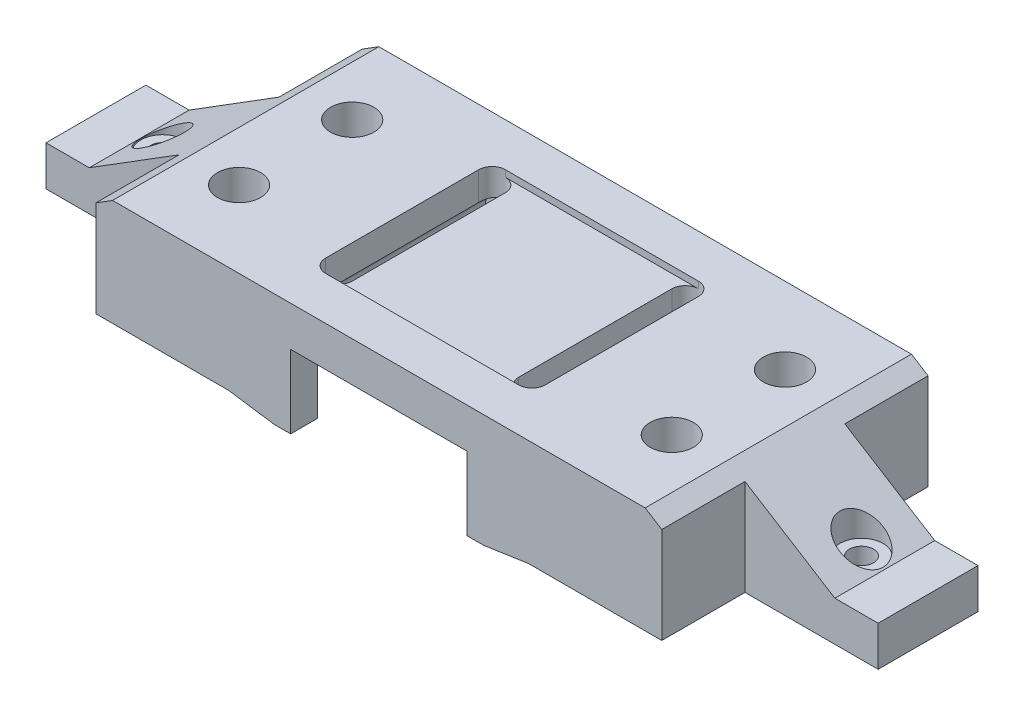
SolidWorks part; units mm, degrees
ref_plane "Front Plane" through (0, 0, 0) normal (0, 0, 1) x (1, 0, 0)
ref_plane "Top Plane" through (0, 0, 0) normal (0, 1, 0) x (1, 0, 0)
ref_plane "Right Plane" through (0, 0, 0) normal (1, 0, 0) x (0, 0, -1)
sketch "Sketch1" plane through (0, 0, 0) normal (0, 1, 0) x (1, 0, 0)
  line L0 (42.5, 20) -> (42.5, 7.5)
  line L1 (-42.5, 20) -> (42.5, 20)
  line L3 (-42.5, -20) -> (42.5, -20)
  line L5 (-42.5, 20) -> (42.5, -20) construction
  line L6 (-42.5, -20) -> (42.5, 20) construction
  line L7 (42.5, 7.5) -> (62.5, 7.5)
  line L8 (62.5, 7.5) -> (62.5, -7.5)
  line L9 (62.5, -7.5) -> (42.5, -7.5)
  line L10 (42.5, -7.5) -> (42.5, -20)
  line L11 (0, 0) -> (0, -116.996) construction
  line L12 (-42.5, -7.5) -> (-42.5, -20)
  line L13 (-62.5, -7.5) -> (-42.5, -7.5)
  line L14 (-62.5, 7.5) -> (-62.5, -7.5)
  line L15 (-42.5, 7.5) -> (-62.5, 7.5)
  line L16 (-42.5, 20) -> (-42.5, 7.5)
  circle A0 centre (-52.5, 0) radius 1.8
  circle A1 centre (-32.5, 8.5) radius 1.8
  circle A2 centre (-32.5, -8.5) radius 1.8
  circle A3 centre (32.5, -8.5) radius 1.8
  circle A4 centre (52.5, 0) radius 1.8
  circle A5 centre (32.5, 8.5) radius 1.8
  point P0 (0, 0)
  dimension "D6" = 3.6
  dimension "D1" = 85
  dimension "D2" = 40
  dimension "D3" = 20
  dimension "D4" = 15
  dimension "D5" = 12.5
  dimension "D7" = 7.5
  dimension "D8" = 10
  dimension "D9" = 10
  dimension "D10" = 1
  dimension "D11" = 10
  dimension "D12" = 1
extrude "Boss-Extrude1" add sketch "Sketch1" along normal blind 6
sketch "Sketch2" plane through (0, 0, -20) normal (0, 0, -1) x (-1, 0, 0)
  line L0 (-56, 6) -> (-40, 16)
  line L1 (-42.5, 6) -> (42.5, 6) construction
  line L2 (-40, 16) -> (40, 16)
  line L3 (40, 16) -> (56, 6)
  line L4 (-62.5, 6) -> (-42.5, 6) construction
  line L5 (-56, 6) -> (56, 6)
  dimension "D1" = 80
  dimension "D2" = 10
  dimension "D3" = 112
  dimension "D4" = 16
  dimension "D5" = 6.5
extrude "Boss-Extrude2" add sketch "Sketch2" against normal up to surface (40 mm away) up to face at (0, 3, 20)
sketch "Sketch3" plane through (0, 6, 0) normal (0, -1, 0) x (1, 0, 0)
  line L0 (-62.5, 7.5) -> (-42.5, 7.5) construction
  line L1 (-56, 20) -> (-42.5, 20)
  line L2 (-56, 20) -> (-56, 7.5)
  line L3 (-56, 7.5) -> (-42.5, 7.5)
  line L4 (-42.5, 20) -> (-42.5, 7.5)
  line L5 (-56, 7.5) -> (-42.5, 7.5) construction
  line L6 (62.5, -7.5) -> (42.5, -7.5) construction
  line L7 (-56, -7.5) -> (-42.5, -7.5)
  line L8 (-56, -7.5) -> (-56, -20)
  line L9 (-56, -20) -> (-42.5, -20)
  line L10 (-42.5, -7.5) -> (-42.5, -20)
  line L11 (42.5, -20) -> (56, -20)
  line L12 (42.5, -20) -> (42.5, -7.5)
  line L13 (42.5, -7.5) -> (56, -7.5)
  line L14 (56, -20) -> (56, -7.5)
  line L15 (56, -7.5) -> (56, -20) construction
  line L17 (56, 7.5) -> (42.5, 7.5)
  line L18 (56, 7.5) -> (56, 20)
  line L19 (56, 20) -> (42.5, 20)
  line L20 (42.5, 7.5) -> (42.5, 20)
  circle A0 centre (52.5, 0) radius 1.8 construction
  circle A1 centre (32.5, -8.5) radius 1.8 construction
  circle A2 centre (32.5, 8.5) radius 1.8 construction
  circle A3 centre (-32.5, -8.5) radius 1.8 construction
  circle A4 centre (-52.5, 0) radius 1.8 construction
  circle A5 centre (-32.5, 8.5) radius 1.8 construction
  circle A6 centre (52.5, 0) radius 1.8
  circle A7 centre (32.5, -8.5) radius 1.8
  circle A8 centre (32.5, 8.5) radius 1.8
  circle A9 centre (-32.5, -8.5) radius 1.8
  circle A10 centre (-52.5, 0) radius 1.8
  circle A11 centre (-32.5, 8.5) radius 1.8
extrude "Cut-Extrude1" cut sketch "Sketch3" against normal up to next
sketch "Sketch4" plane through (0, 16, 0) normal (0, 1, 0) x (1, 0, 0)
  circle A0 centre (-32.5, 8.5) radius 3.25
  circle A1 centre (-52.5, 0) radius 3.25
  circle A2 centre (-32.5, -8.5) radius 3.25
  circle A3 centre (32.5, 8.5) radius 3.25
  circle A4 centre (32.5, -8.5) radius 3.25
  circle A5 centre (52.5, 0) radius 3.25
  dimension "D1" = 6.5
extrude "Cut-Extrude2" cut sketch "Sketch4" against normal up to surface (10 mm away) up to face at (-59.25, 6, 0)
sketch "Sketch5" plane through (0, 0, -20) normal (0, 0, -1) x (-1, 0, 0)
  line L0 (-22.5, 0) -> (-16, 10)
  line L1 (-42.5, 0) -> (42.5, 0) construction
  line L2 (-16, 10) -> (16, 10)
  line L3 (16, 10) -> (22.5, 0)
  line L4 (22.5, 0) -> (-22.5, 0)
  dimension "D5" = 6.5
  dimension "D1" = 45
  dimension "D2" = 20
  dimension "D3" = 10
  dimension "D4" = 32
extrude "Cut-Extrude3" cut sketch "Sketch5" against normal up to next
sketch "Sketch6" plane through (0, 10, 0) normal (0, -1, 0) x (1, 0, 0)
  line L1 (-17.5, 13.5) -> (17.5, 13.5)
  line L2 (-17.5, 13.5) -> (-17.5, -13.5)
  line L3 (-17.5, -13.5) -> (17.5, -13.5)
  line L4 (17.5, 13.5) -> (17.5, -13.5)
  dimension "D1" = 27
  dimension "D2" = 13.5
  dimension "D3" = 35
  dimension "D4" = 17.5
extrude "Cut-Extrude4" cut sketch "Sketch6" against normal blind 2 and the other way up to next
fillet "Fillet1" radius 2 2 edges at (17.5, 12, 0) (-17.5, 12, 0)
sketch "Sketch7" plane through (0, 0, -20) normal (0, 0, -1) x (-1, 0, 0)
  line L0 (-22.5, 0) -> (-15.75, -1)
  line L1 (-16, 10) -> (-22.5, 0) construction
  line L2 (-15.75, -1) -> (-13.25, -1)
  line L3 (-13.25, -1) -> (-13.25, 10)
  line L4 (16, 10) -> (-16, 10) construction
  line L5 (-13.25, 10) -> (-16, 10)
  line L6 (-16, 10) -> (-22.5, 0)
  line L7 (0, 0) -> (0, -17.4167) construction
  line L8 (16, 10) -> (22.5, 0)
  line L9 (13.25, 10) -> (16, 10)
  line L10 (13.25, -1) -> (13.25, 10)
  line L11 (15.75, -1) -> (13.25, -1)
  line L12 (22.5, 0) -> (15.75, -1)
  point P18 (-16, -3.328)
  point P19 (-16, -3.1377)
  point P20 (-22.5, 0)
  dimension "D1" = 26.5
  dimension "D2" = 11
  dimension "D3" = 2.5
extrude "Boss-Extrude3" add sketch "Sketch7" against normal blind 4
mirror "Mirror1" about plane through (0, 0, 0) normal (0, 0, 1) of "Boss-Extrude3"
sketch "Sketch8" plane through (0, 12, 0) normal (0, -1, 0) x (1, 0, 0)
  line L0 (-14.5, 11.5) -> (-14.5, -11.5) construction
  line L1 (-12.5, 11.5) -> (-12.5, -11.5)
  line L2 (-16.5, 11.5) -> (-16.5, -11.5)
  line L3 (14.5, 11.5) -> (14.5, -11.5) construction
  line L4 (16.5, 11.5) -> (16.5, -11.5)
  line L5 (12.5, 11.5) -> (12.5, -11.5)
  arc A0 (-12.5, 11.5) -> (-16.5, 11.5) centre (-14.5, 11.5) ccw
  arc A1 (-16.5, -11.5) -> (-12.5, -11.5) centre (-14.5, -11.5) ccw
  arc A2 (16.5, 11.5) -> (12.5, 11.5) centre (14.5, 11.5) ccw
  arc A3 (12.5, -11.5) -> (16.5, -11.5) centre (14.5, -11.5) ccw
  point P2 (-14.5, 0)
  point P7 (14.5, 0)
  point P14 (0, 0)
  point P15 (0, 0)
  dimension "D1" = 2
  dimension "D2" = 2
  dimension "D3" = 29
  dimension "D4" = 14.5
  dimension "D5" = 23
  dimension "D6" = 23
extrude "Cut-Extrude5" cut sketch "Sketch8" against normal up to next and the other way up to next
sketch "Sketch9" plane through (0, 0, 16) normal (0, 0, -1) x (-1, 0, 0)
  line L1 (-13.25, 10) -> (-22.5, 10)
  line L2 (-13.25, 10) -> (-13.25, 0)
  line L3 (-13.25, 0) -> (-22.5, 0)
  line L4 (-22.5, 10) -> (-22.5, 0)
extrude "Cut-Extrude6" cut sketch "Sketch9" along normal up to surface (32 mm away) up to face at (16.15, 3.6, -16)
sketch "Sketch10" plane through (0, 16, 0) normal (0, 1, 0) x (1, 0, 0)
  line L1 (-14.5, 13.5) -> (14.5, 13.5)
  line L2 (-14.5, 13.5) -> (-14.5, -13.5)
  line L3 (-14.5, -13.5) -> (14.5, -13.5)
  line L4 (14.5, 13.5) -> (14.5, -13.5)
  arc A0 (-12.5, 11.5) -> (-16.5, 11.5) centre (-14.5, 11.5) ccw construction
  arc A1 (12.5, -11.5) -> (16.5, -11.5) centre (14.5, -11.5) ccw construction
extrude "Cut-Extrude7" cut sketch "Sketch10" against normal blind 1
equation "\"D5@Sketch1\"=(\"D2@Sketch1\"-\"D4@Sketch1\")/2"
equation "\"D4@Sketch2\"=(\"D3@Sketch2\"-\"D1@Sketch2\")/2"
equation "\"D5@Sketch2\"=(125-\"D3@Sketch2\")/2"
equation "\"D2@Sketch5\"=(85-\"D1@Sketch5\")/2"
equation "\"D5@Sketch5\"=(\"D1@Sketch5\"-\"D4@Sketch5\")/2"
equation "\"D2@Sketch6\"=\"D1@Sketch6\"/2"
equation "\"D4@Sketch8\"=\"D3@Sketch8\"/2"
